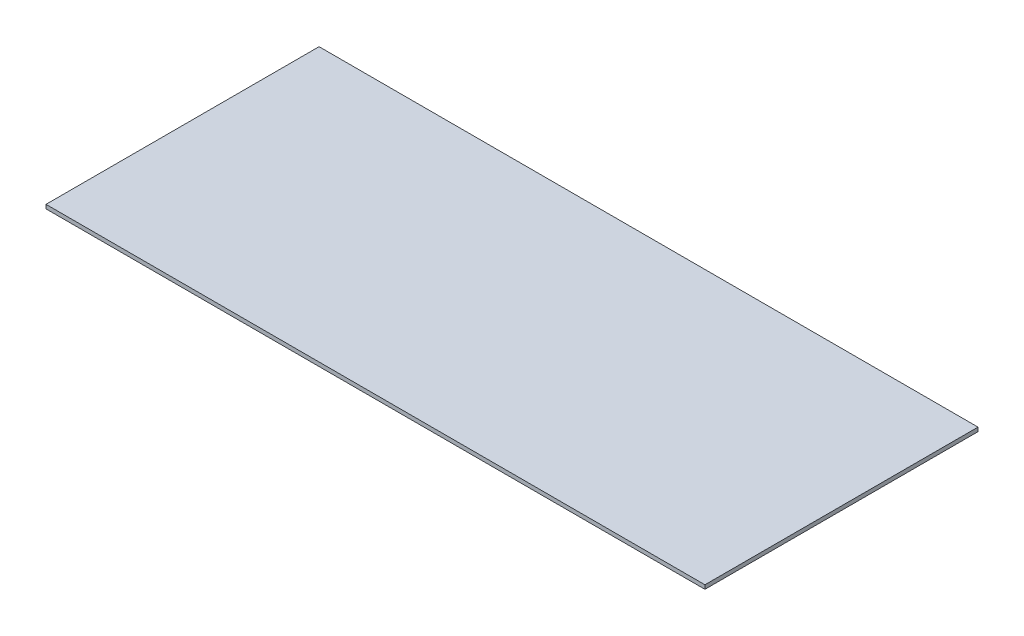
SolidWorks part; units mm, degrees
material "Maple"
ref_plane "Front Plane" through (0, 0, 0) normal (0, 0, 1) x (1, 0, 0)
ref_plane "Top Plane" through (0, 0, 0) normal (0, 1, 0) x (1, 0, 0)
ref_plane "Right Plane" through (0, 0, 0) normal (1, 0, 0) x (0, 0, -1)
sketch "Sketch1" plane through (0, 0, 0) normal (0, 1, 0) x (1, 0, 0)
  line L1 (0, 0) -> (2114.55, 0)
  line L2 (0, 0) -> (0, 876.3)
  line L3 (0, 876.3) -> (2114.55, 876.3)
  line L4 (2114.55, 0) -> (2114.55, 876.3)
  dimension "D1" = 876.3
  dimension "D2" = 2114.55
extrude "Boss-Extrude1" add sketch "Sketch1" along normal blind 12.7
